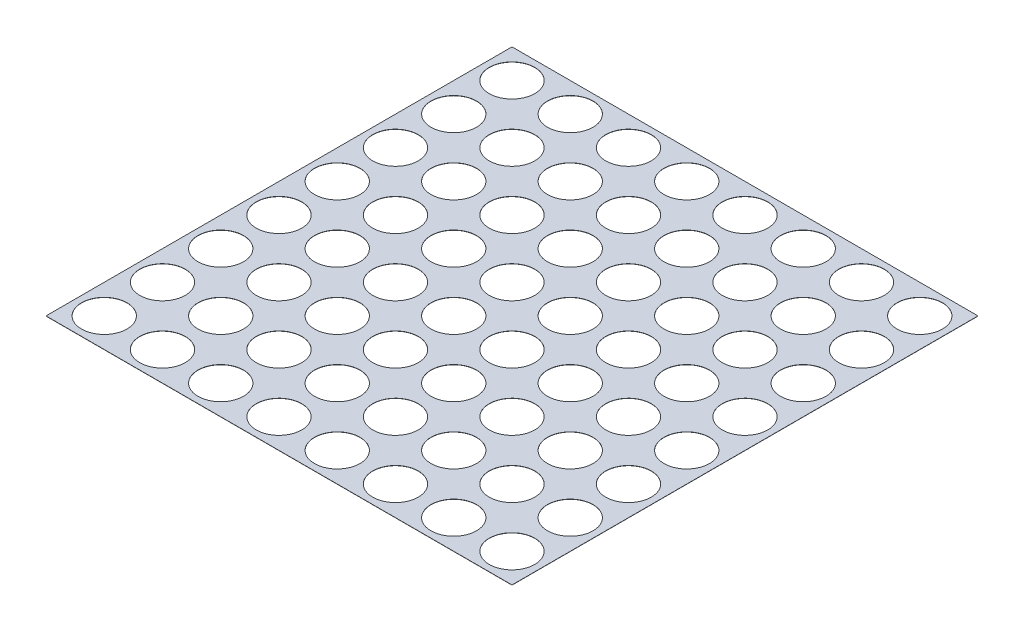
SolidWorks part; units mm, degrees
material "Mogno"
ref_plane "Plano frontal" through (0, 0, 0) normal (0, 0, 1) x (1, 0, 0)
ref_plane "Plano superior" through (0, 0, 0) normal (0, 1, 0) x (1, 0, 0)
ref_plane "Plano direito" through (0, 0, 0) normal (1, 0, 0) x (0, 0, -1)
sketch "Esboço1" plane through (0, 0, 0) normal (0, 1, 0) x (1, 0, 0)
  line L1 (-128, 128) -> (128, 128)
  line L2 (-128, 128) -> (-128, -128)
  line L3 (-128, -128) -> (128, -128)
  line L4 (128, 128) -> (128, -128)
  line L5 (-128, 128) -> (128, -128) construction
  line L6 (-128, -128) -> (128, 128) construction
  point P0 (0, 0)
  dimension "D1" = 256
extrude "Ressalto-extrusão1" add sketch "Esboço1" along normal blind 0.1
sketch "Esboço2" plane through (0, 0.1, 0) normal (0, 1, 0) x (1, 0, 0)
  line L0 (-32, 128) -> (-32, -128) construction
  line L1 (-128, 128) -> (128, 128) construction
  line L2 (-128, 128) -> (-128, -128) construction
  line L3 (-128, -128) -> (128, -128) construction
  line L4 (128, 128) -> (128, -128) construction
  line L5 (-128, 128) -> (128, -128) construction
  line L6 (-128, -128) -> (128, 128) construction
  line L7 (-64, 128) -> (-64, -128) construction
  line L8 (0, 128) -> (0, -128) construction
  line L9 (-96, 128) -> (-96, -128) construction
  line L10 (32, 128) -> (32, -128) construction
  line L11 (64, 128) -> (64, -128) construction
  line L12 (96, 128) -> (96, -128) construction
  line L13 (-128, 96) -> (128, 96) construction
  line L14 (-128, 64) -> (128, 64) construction
  line L15 (-128, 32) -> (128, 32) construction
  line L16 (-128, 0) -> (128, 0) construction
  line L17 (-128, -32) -> (128, -32) construction
  line L18 (-128, -64) -> (128, -64) construction
  line L19 (-128, -96) -> (128, -96) construction
  circle A0 centre (-112, -112) radius 12.5
  circle A1 centre (-80, -112) radius 12.5
  circle A2 centre (-48, -112) radius 12.5
  circle A3 centre (-16, -112) radius 12.5
  circle A4 centre (16, -112) radius 12.5
  circle A5 centre (48, -112) radius 12.5
  circle A6 centre (80, -112) radius 12.5
  circle A7 centre (112, -112) radius 12.5
  circle A8 centre (112, -80) radius 12.5
  circle A9 centre (80, -80) radius 12.5
  circle A10 centre (48, -80) radius 12.5
  circle A11 centre (16, -80) radius 12.5
  circle A12 centre (-16, -80) radius 12.5
  circle A13 centre (-48, -80) radius 12.5
  circle A14 centre (-80, -80) radius 12.5
  circle A15 centre (-112, -80) radius 12.5
  circle A16 centre (112, -16) radius 12.5
  circle A17 centre (112, -48) radius 12.5
  circle A18 centre (80, -16) radius 12.5
  circle A19 centre (80, -48) radius 12.5
  circle A20 centre (48, -16) radius 12.5
  circle A21 centre (48, -48) radius 12.5
  circle A22 centre (16, -16) radius 12.5
  circle A23 centre (16, -48) radius 12.5
  circle A24 centre (-16, -16) radius 12.5
  circle A25 centre (-16, -48) radius 12.5
  circle A26 centre (-48, -16) radius 12.5
  circle A27 centre (-48, -48) radius 12.5
  circle A28 centre (-80, -16) radius 12.5
  circle A29 centre (-80, -48) radius 12.5
  circle A30 centre (-112, -48) radius 12.5
  circle A31 centre (-112, -16) radius 12.5
  circle A32 centre (-112, 16) radius 12.5
  circle A33 centre (-80, 16) radius 12.5
  circle A34 centre (-48, 16) radius 12.5
  circle A35 centre (-16, 16) radius 12.5
  circle A36 centre (16, 16) radius 12.5
  circle A37 centre (48, 16) radius 12.5
  circle A38 centre (80, 16) radius 12.5
  circle A39 centre (112, 16) radius 12.5
  circle A40 centre (112, 48) radius 12.5
  circle A41 centre (80, 48) radius 12.5
  circle A42 centre (48, 48) radius 12.5
  circle A43 centre (16, 48) radius 12.5
  circle A44 centre (-16, 48) radius 12.5
  circle A45 centre (-48, 48) radius 12.5
  circle A46 centre (-80, 48) radius 12.5
  circle A47 centre (-112, 48) radius 12.5
  circle A48 centre (-112, 80) radius 12.5
  circle A49 centre (-80, 80) radius 12.5
  circle A50 centre (-48, 80) radius 12.5
  circle A51 centre (-16, 80) radius 12.5
  circle A52 centre (16, 80) radius 12.5
  circle A53 centre (48, 80) radius 12.5
  circle A54 centre (80, 80) radius 12.5
  circle A55 centre (112, 80) radius 12.5
  circle A56 centre (112, 112) radius 12.5
  circle A57 centre (80, 112) radius 12.5
  circle A58 centre (48, 112) radius 12.5
  circle A59 centre (16, 112) radius 12.5
  circle A60 centre (-16, 112) radius 12.5
  circle A61 centre (-48, 112) radius 12.5
  circle A62 centre (-80, 112) radius 12.5
  circle A63 centre (-112, 112) radius 12.5
  point P0 (0, 0)
  dimension "D4" = 25
  dimension "D1" = 256
  dimension "D2" = 32
  dimension "D3" = 32
  dimension "D5" = 16
  dimension "D6" = 16
extrude "Corte-extrusão1" cut sketch "Esboço2" against normal through all
